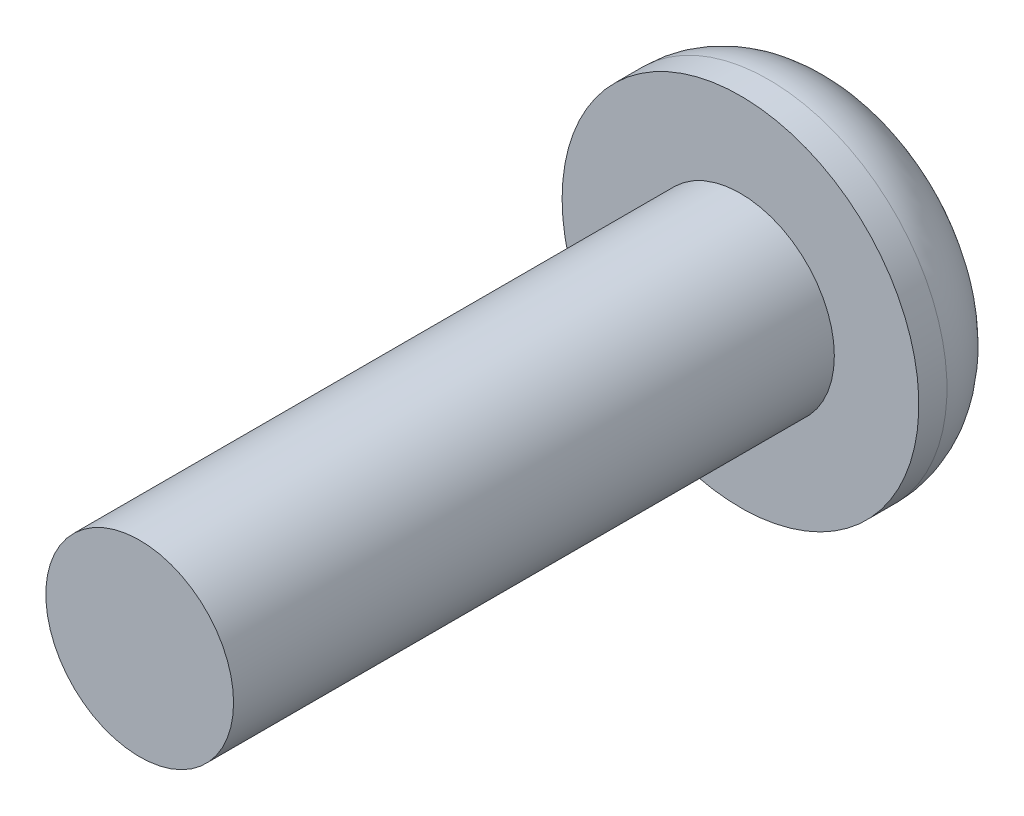
SolidWorks part; units mm, degrees
ref_plane "前视基准面" through (0, 0, 0) normal (0, 0, 1) x (1, 0, 0)
ref_plane "上视基准面" through (0, 0, 0) normal (0, 1, 0) x (1, 0, 0)
ref_plane "右视基准面" through (0, 0, 0) normal (1, 0, 0) x (0, 0, -1)
sketch "草图1" plane through (0, 0, 0) normal (0, 0, 1) x (1, 0, 0)
  circle A0 centre (0, 0) radius 2.5
extrude "凸台-拉伸1" add sketch "草图1" along normal blind 16
sketch "草图2" plane through (0, 0, 0) normal (0, 0, -1) x (-1, 0, 0)
  circle A0 centre (0, 0) radius 4.75
extrude "凸台-拉伸2" add sketch "草图2" along normal blind 2.75
fillet "圆角1" radius 2 1 edges at (-4.75, 0, -2.75)
